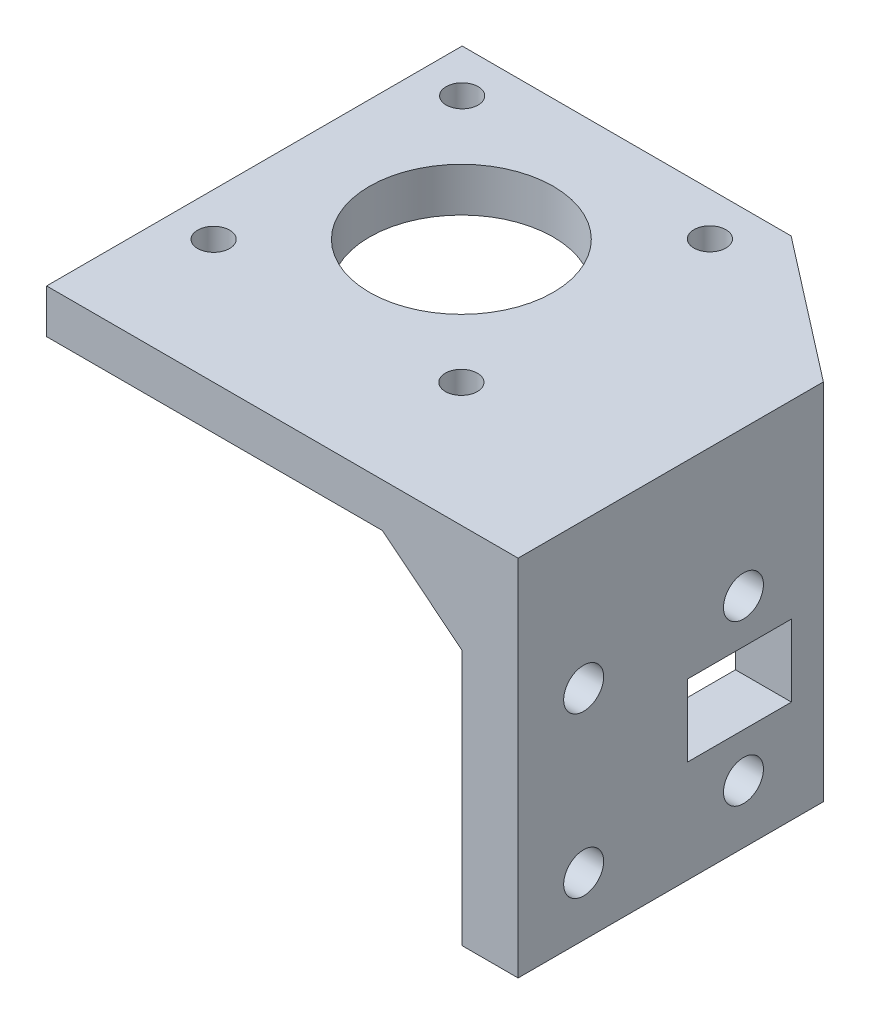
SolidWorks part; units mm, degrees
ref_plane "Front Plane" through (0, 0, 0) normal (0, 0, 1) x (1, 0, 0)
ref_plane "Top Plane" through (0, 0, 0) normal (0, 1, 0) x (1, 0, 0)
ref_plane "Right Plane" through (0, 0, 0) normal (1, 0, 0) x (0, 0, -1)
sketch "Sketch1" plane through (0, 0, 0) normal (0, 1, 0) x (1, 0, 0)
  line L1 (0, 0) -> (-59, 0)
  line L2 (0, 0) -> (0, -52)
  line L3 (0, -52) -> (-59, -52)
  line L4 (-59, 0) -> (-59, -52)
  dimension "D1" = 52
  dimension "D2" = 59
extrude "Boss-Extrude1" add sketch "Sketch1" along normal blind 5.5
sketch "Sketch2" plane through (0, 5.5, 0) normal (0, 1, 0) x (1, 0, 0)
  line L0 (-59, 0) -> (-59, -52) construction
  line L1 (0, 0) -> (-59, 0) construction
  line L3 (-59, -52) -> (0, -52) construction
  circle A0 centre (-53.6, -5.4) radius 2
  circle A1 centre (-22.6, -5.4) radius 2
  circle A2 centre (-53.6, -36.5) radius 2
  circle A3 centre (-22.6, -36.5) radius 2
  dimension "D5" = 15.5
  dimension "D9" = 4
  dimension "D10" = 4
  dimension "D11" = 4
  dimension "D12" = 4
  dimension "D1" = 5.4
  dimension "D2" = 5.4
  dimension "D3" = 5.4
  dimension "D4" = 31
  dimension "D6" = 5.4
  dimension "D7" = 31
  dimension "D8" = 15.5
extrude "Cut-Extrude1" cut sketch "Sketch2" against normal blind 10
sketch "Sketch4" plane through (0, 0, 0) normal (0, -1, 0) x (-1, 0, 0)
  line L0 (59, -52) -> (0, -52) construction
  line L1 (0, 0) -> (7, 0)
  line L2 (0, 0) -> (0, -52)
  line L3 (0, -52) -> (7, -52)
  line L4 (7, 0) -> (7, -52)
  dimension "D1" = 7
extrude "Boss-Extrude3" add sketch "Sketch4" along normal blind 40
sketch "Sketch5" plane through (-7, 0, 0) normal (-1, 0, 0) x (0, 0, 1)
  line L0 (52, -40) -> (52, 0) construction
  line L1 (52, -40) -> (0, -40) construction
  circle A0 centre (43.8, -32.7) radius 2.5
  circle A1 centre (43.8, -12.7) radius 2.5
  circle A2 centre (23.8, -32.7) radius 2.5
  circle A3 centre (23.8, -12.7) radius 2.5
  dimension "D3" = 5
  dimension "D4" = 5
  dimension "D7" = 5
  dimension "D8" = 5
  dimension "D1" = 8.2
  dimension "D2" = 7.3
  dimension "D5" = 20
  dimension "D6" = 0
  dimension "D9" = 20
  dimension "D10" = 20
  dimension "D11" = 20
  dimension "D12" = 7.3
extrude "Cut-Extrude2" cut sketch "Sketch5" against normal blind 33
sketch "Sketch6" plane through (-7, 0, 0) normal (-1, 0, 0) x (0, 0, 1)
  line L0 (52, 0) -> (0, 0) construction
  line L1 (0, -40) -> (13.8, -40)
  line L2 (0, -40) -> (0, 0)
  line L3 (0, 0) -> (13.8, 0)
  line L4 (13.8, -40) -> (13.8, 0)
  circle A0 centre (23.8, -32.7) radius 2.5 construction
  dimension "D1" = 10
extrude "Cut-Extrude3" cut sketch "Sketch6" against normal blind 33
sketch "Sketch7" plane through (0, 0, 0) normal (0, -1, 0) x (-1, 0, 0)
  line L0 (0, 0) -> (0, -13.8)
  line L1 (0, -13.8) -> (17.8364, 0)
  line L2 (0, 0) -> (59, 0) construction
  line L3 (17.8364, 0) -> (0, 0)
extrude "Cut-Extrude4" cut sketch "Sketch7" against normal blind 33
sketch "Sketch8" plane through (0, 0, 52) normal (0, 0, 1) x (1, 0, 0)
  line L0 (-7, 0) -> (-7, -8)
  line L1 (-7, -40) -> (-7, 0) construction
  line L2 (-7, -8) -> (-17, 0)
  line L3 (-59, 0) -> (-7, 0) construction
  line L4 (-17, 0) -> (-7, 0)
  dimension "D1" = 8
  dimension "D2" = 10
extrude "Boss-Extrude6" add sketch "Sketch8" against normal up to vertex (38.2 mm away) up to point (-7, -40, 13.8)
sketch "Sketch10" plane through (-7, 0, 0) normal (-1, 0, 0) x (0, 0, 1)
  line L1 (17.8, -18.2) -> (30.8, -18.2)
  line L2 (17.8, -18.2) -> (17.8, -27.2)
  line L3 (17.8, -27.2) -> (30.8, -27.2)
  line L4 (30.8, -18.2) -> (30.8, -27.2)
  line L5 (13.8, -40) -> (13.8, -8) construction
  circle A0 centre (23.8, -32.7) radius 2.5 construction
  circle A1 centre (23.8, -12.7) radius 2.5 construction
  dimension "D1" = 5.5
  dimension "D2" = 7
  dimension "D3" = 5.5
  dimension "D4" = 4
extrude "Cut-Extrude8" cut sketch "Sketch10" against normal blind 10
sketch "Sketch11" plane through (0, 5.5, 0) normal (0, 1, 0) x (1, 0, 0)
  circle A0 centre (-38.1, -21) radius 11.5
  circle A1 centre (-22.6, -36.5) radius 2 construction
  circle A2 centre (-53.6, -36.5) radius 2 construction
  dimension "D3" = 23
  dimension "D1" = 15.5
  dimension "D2" = 15.5
extrude "Cut-Extrude9" cut sketch "Sketch11" against normal blind 10
